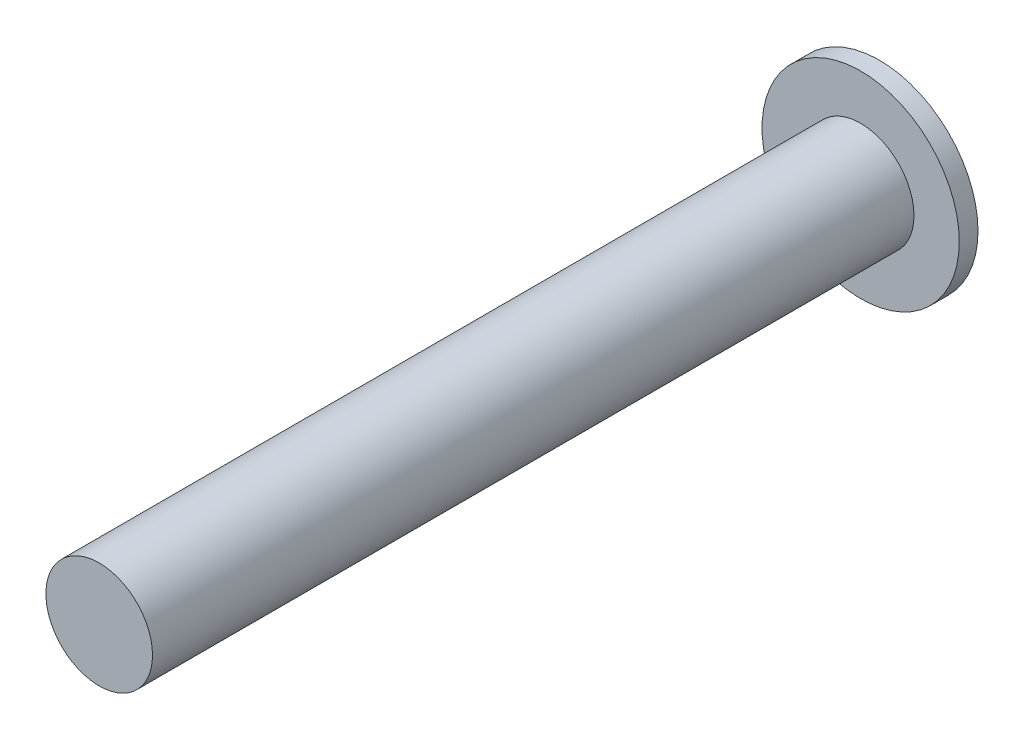
SolidWorks part; units mm, degrees
ref_plane "Front Plane" through (0, 0, 0) normal (0, 0, 1) x (1, 0, 0)
ref_plane "Top Plane" through (0, 0, 0) normal (0, 1, 0) x (1, 0, 0)
ref_plane "Right Plane" through (0, 0, 0) normal (1, 0, 0) x (0, 0, -1)
sketch "Sketch2" plane through (0, 0, 0) normal (0, 0, 1) x (1, 0, 0)
  circle A0 centre (0, 0) radius 6.475
  dimension "D1" = 12.95
extrude "Boss-Extrude1" add sketch "Sketch2" along normal blind 1.23
sketch "Sketch4" plane through (0, 0, 1.23) normal (0, 0, 1) x (1, 0, 0)
  circle A0 centre (0, 0) radius 3.5
  dimension "D1" = 7
extrude "Boss-Extrude2" add sketch "Sketch4" along normal blind 50
